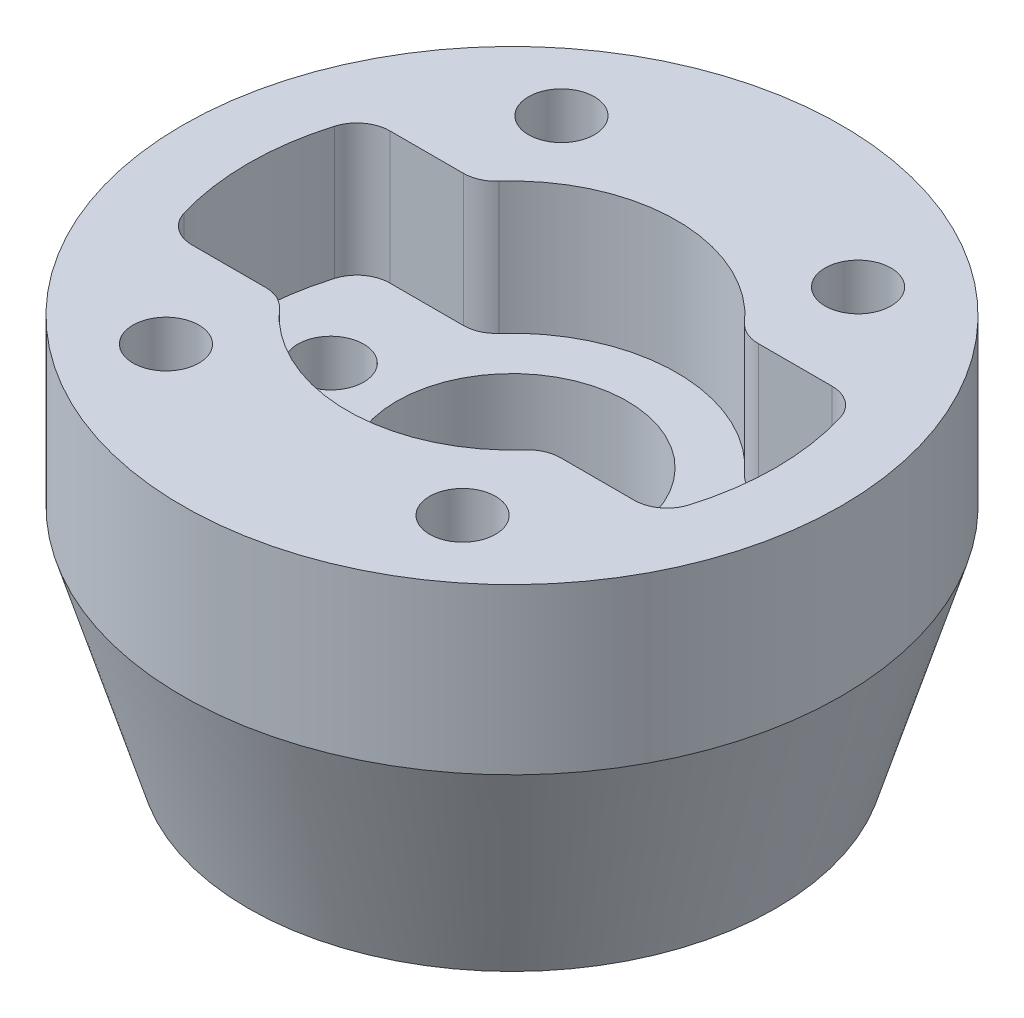
SolidWorks part; units mm, degrees
ref_plane "前视基准面" through (0, 0, 0) normal (0, 0, 1) x (1, 0, 0)
ref_plane "上视基准面" through (0, 0, 0) normal (0, 1, 0) x (1, 0, 0)
ref_plane "右视基准面" through (0, 0, 0) normal (1, 0, 0) x (0, 0, -1)
other "Configuration Table"
sketch "草图1" plane through (0, 0, 0) normal (0, 0, 1) x (1, 0, 0)
  line L0 (0, 0.2861) -> (0, -0.3601) construction
  line L1 (2, 0) -> (2, 2)
  line L2 (2, 0) -> (2.2, 0)
  line L3 (2.2, 0) -> (2.8314, 0.1) construction
  line L4 (2.2, 0) -> (8, 0.9186)
  line L5 (2, 2) -> (3, 2)
  line L6 (3, 2) -> (3, 4)
  line L7 (3, 4) -> (3.5, 4)
  line L8 (3.5, 4) -> (3.5, 12.5)
  line L11 (10, 7.5) -> (10, 12.5)
  line L15 (3.5, 12.5) -> (10, 12.5)
  line L16 (8, 0.9186) -> (10, 7.5)
  dimension "D1" = 9
  dimension "D2" = 0.1
  dimension "D3" = 2
  dimension "D4" = 2
  dimension "D5" = 0.2
  dimension "D6" = 8
  dimension "D7" = 2
  dimension "D8" = 3
  dimension "D9" = 8.5
  dimension "D10" = 7
  dimension "D11" = 5
  dimension "D12" = 10
revolve "旋转1" add sketch "草图1" angle 360 about L0
sketch "草图2" plane through (0, 12.5, 0) normal (0, 1, 0) x (1, 0, 0)
  line L0 (-7.4162, 3) -> (-4, 3)
  line L1 (-55, 0) -> (55, 0) construction
  line L2 (-7.4162, -3) -> (-4, -3)
  line L3 (0, -55) -> (0, 55) construction
  line L4 (7.4162, -3) -> (4, -3)
  line L5 (7.4162, 3) -> (4, 3)
  arc A0 (-4, -3) -> (4, -3) centre (0, 0) ccw
  arc A1 (-7.4162, 3) -> (-7.4162, -3) centre (0, 0) ccw
  circle A2 centre (0, 0) radius 10 construction
  arc A3 (4, 3) -> (-4, 3) centre (0, 0) ccw
  arc A4 (7.4162, -3) -> (7.4162, 3) centre (0, 0) ccw
  dimension "D1" = 10
  dimension "D2" = 2
  dimension "D3" = 3
extrude "切除-拉伸1" cut sketch "草图2" against normal blind 4
fillet "圆角1" radius 1 8 edges at (4, 10.5, 3) (7.4162, 10.5, 3) (7.4162, 10.5, -3) (4, 10.5, -3) (-4, 10.5, 3) (-7.4162, 10.5, 3) (-4, 10.5, -3) (-7.4162, 10.5, -3)
sketch "草图3" plane through (0, 8.5, 0) normal (0, 1, 0) x (1, 0, 0)
  line L0 (0, -55) -> (0, 55) construction
  circle A1 centre (5.5, 0) radius 1
  circle A2 centre (-5.5, 0) radius 1
  point P4 (0, 0)
  dimension "D1" = 5.5
  dimension "D2" = 2
extrude "切除-拉伸2" cut sketch "草图3" against normal blind 4
sketch "草图4" plane through (0, 12.5, 0) normal (0, 1, 0) x (1, 0, 0)
  line L1 (4.5, 6) -> (-4.5, 6) construction
  line L2 (4.5, 6) -> (4.5, -6) construction
  line L3 (4.5, -6) -> (-4.5, -6) construction
  line L4 (-4.5, 6) -> (-4.5, -6) construction
  line L5 (4.5, 6) -> (-4.5, -6) construction
  line L6 (4.5, -6) -> (-4.5, 6) construction
  circle A2 centre (-4.5, 6) radius 1
  circle A3 centre (4.5, 6) radius 1
  circle A4 centre (-4.5, -6) radius 1
  circle A5 centre (4.5, -6) radius 1
  point P0 (0, 0)
  dimension "D1" = 2
  dimension "D4" = 2
  dimension "D5" = 2
  dimension "D6" = 2
  dimension "D2" = 9
  dimension "D3" = 12
extrude "切除-拉伸3" cut sketch "草图4" against normal blind 4
